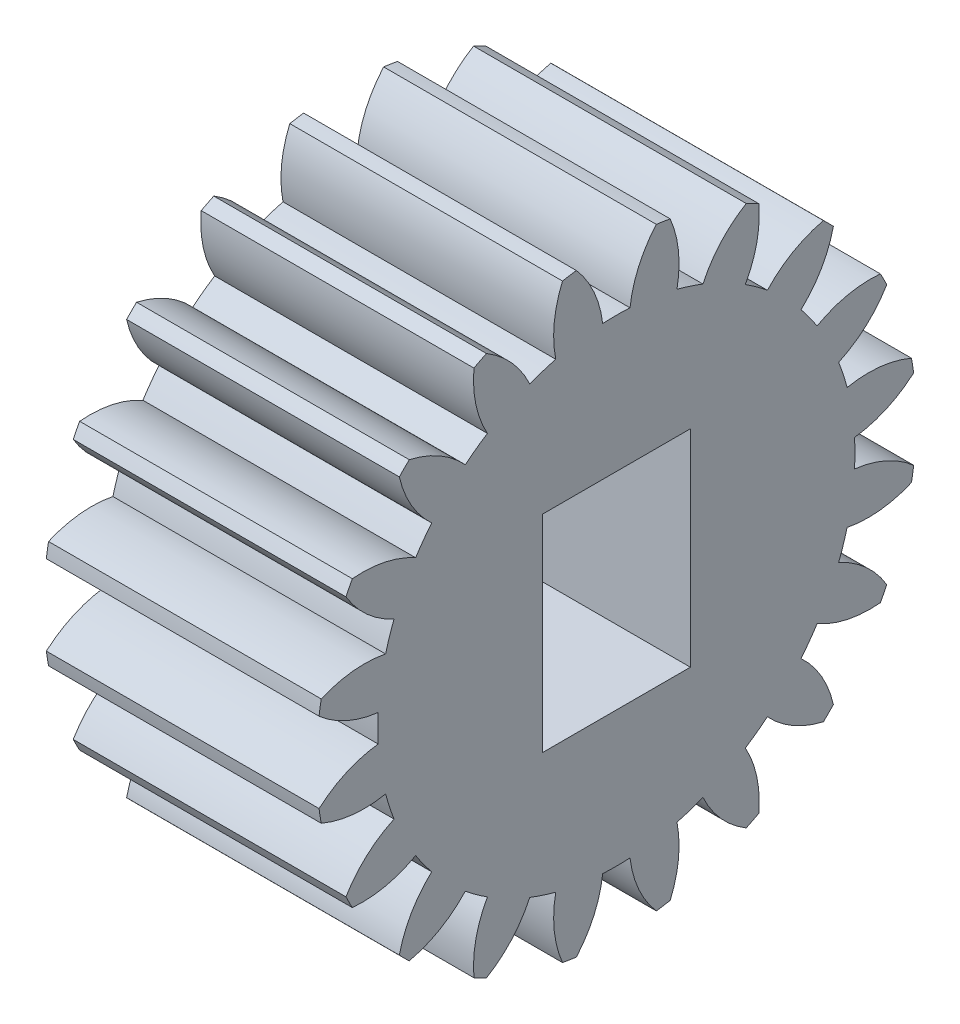
SolidWorks part; units mm, degrees
ref_plane "Plane1" through (0, 0, 0) normal (0, 0, 1) x (1, 0, 0)
ref_plane "Plane2" through (0, 0, 0) normal (0, 1, 0) x (1, 0, 0)
ref_plane "Plane3" through (0, 0, 0) normal (1, 0, 0) x (0, 0, -1)
other "Configuration Table"
sketch "HoldingSke" plane through (0, 0, 0) normal (0, 1, 0) x (1, 0, 0)
  line L0 (0, 0) -> (1.3424, -0.4886)
  line L1 (-15, 0) -> (100, 0) construction
  line L2 (0, 0) -> (-2.1039, 2.3779)
  line L3 (0, 0) -> (-11.863, 4.5341)
  line L4 (0, 0) -> (8.1152, 2.9537)
  line L5 (0, 0) -> (-46.8476, -17.4728)
  line L6 (0, 0) -> (-5.8027, -3.9151)
  line L7 (-2.1039, 2.3779) -> (8.6586, 51.2059)
  line L8 (-76.2, 54.61) -> (-76.1, 54.61)
  line L9 (-71.009, 38.7566) -> (-53.1078, 45.2721)
  line L10 (-76.2, 71.12) -> (104.1128, 71.12)
  line L11 (0, 0) -> (-7, 0)
  line L12 (-76.2, 101.6) -> (-76.173, 101.6)
  line L13 (24.9733, 27.94) -> (52.9518, 28.4284)
  line L14 (24.9733, 27.94) -> (24.9743, 27.94)
  line L15 (24.9733, 27.94) -> (100.4006, 29.5858)
  line L16 (-63.627, -0.7) -> (-12.827, -0.7)
  circle A0 centre (0, 0) radius 0.5
  circle A1 centre (0, 0) radius 6.124
  circle A2 centre (0, 0) radius 37.5
  circle A3 centre (0, 0) radius 0.5
  dimension "MHD" = 12.248
  dimension "Hub_dia" = 75
  dimension "Bore" = 1
  dimension "MBD" = 1
  dimension "Num_teeth" = 20
  dimension "Pitch" = 1.4286
  dimension "Overall_len" = 50
  dimension "Show_teeth" = 20
  dimension "Thickness" = 7
  dimension "OAL" = 50.0001
  dimension "T_dim" = 0.1
  dimension "Ap" = 20
  dimension "H" = 19.05
  dimension "Pitch_radius" = 180.3128
  dimension "Width" = 7
  dimension "Backlash" = 0.027
  dimension "Addendum_fac" = 1
  dimension "Dedendum_fac" = 1.25
  dimension "Clearance_fac" = 0.25
  dimension "Dedendum_add" = 0.001
  dimension "Module" = 0.7
sketch "BasProSke" plane through (0, 0, 0) normal (0, 1, 0) x (1, 0, 0)
  line L0 (-10, 0) -> (60, 0) construction
  line L1 (0, 0) -> (0, 7.7)
  line L2 (0, 0) -> (7, 0)
  line L3 (7, 0) -> (7, 7.7)
  line L4 (7, 7.7) -> (0, 7.7)
  dimension "Thickness" = 7
  dimension "Diameter" = 15.4
revolve "Base-Revolve" add sketch "BasProSke" angle 360 about L0
sketch "TooCutSke" plane through (0, 0, 0) normal (1, 0, 0) x (0, 0, -1)
  line L1 (0, 0) -> (0, 107) construction
  line L2 (0, 0) -> (-0.5964, 6.9745) construction
  line L3 (0, 0) -> (-2.1844, 13.792) construction
  line L4 (-0.5964, 6.9745) -> (-1.0922, 6.896) construction
  arc A0 (0.3505, 6.114) -> (-0.3505, 6.114) centre (0, 0) ccw
  arc A1 (1.0465, 7.6542) -> (-1.0465, 7.6542) centre (0, 0) ccw
  circle A2 centre (0, 0) radius 7 construction
  circle A3 centre (0, 0) radius 6.5778 construction
  arc A4 (-0.3505, 6.114) -> (-1.0465, 7.6542) centre (-3.1311, 5.7848) ccw
  arc A5 (1.0465, 7.6542) -> (0.3505, 6.114) centre (3.1311, 5.7848) ccw
  dimension "Root_dia" = 12.248
  dimension "Overcut_dia" = 15.4508
  dimension "Pitch_dia" = 14
  dimension "Base_dia" = 13.1557
  dimension "Flank_rad" = 2.8
  dimension "Half_ang" = 9
  dimension "Half_CT" = 0.502
extrude "ToothCut" cut sketch "TooCutSke" along normal through all
fillet "Breaks" [suppressed] radius 0.014
fillet "RootFillets" [suppressed] radius 0.176
pattern_circular "TeethCuts" count 20 every 18 about axis through (-10, 0, 0) along (1, 0, 0) of "ToothCut", "RootFillets", "Breaks"
sketch "HubNeaOneSke" plane through (0, 0, 0) normal (-1, 0, 0) x (0, 0, 1)
  circle A0 centre (0, 0) radius 6.124
  dimension "Diameter" = 12.248
extrude "HubNearOne" [suppressed] add sketch "HubNeaOneSke" along normal blind 43.0001
sketch "HubNeaBotSke" plane through (0, 0, 0) normal (-1, 0, 0) x (0, 0, 1)
  circle A0 centre (0, 0) radius 6.124
  dimension "Diameter" = 12.248
extrude "HubNearBoth" [suppressed] add sketch "HubNeaBotSke" along normal blind 21.5
ref_plane "FarPln" through (7, 0, 0) normal (1, 0, 0) x (0, 0, -1)
sketch "HubFarSke" plane through (7, 0, 0) normal (1, 0, 0) x (0, 0, -1)
  circle A0 centre (0, 0) radius 6.124
  dimension "Diameter" = 12.248
extrude "HubFar" [suppressed] add sketch "HubFarSke" along normal blind 21.5
sketch "BorSke" plane through (0, 0, 0) normal (1, 0, 0) x (0, 0, -1)
  circle A0 centre (0, 0) radius 0.5
  dimension "Diameter" = 1
extrude "Bore" cut sketch "BorSke" along normal mid plane 100.0001
sketch "KeySke" plane through (0, 0, 0) normal (1, 0, 0) x (0, 0, -1)
  line L0 (-0.05, 0) -> (-0.05, 0.6)
  line L1 (-0.05, 0.6) -> (0.05, 0.6)
  line L2 (0.05, 0.6) -> (0.05, 0)
  line L3 (0, 0) -> (0, 34) construction
  line L4 (-0.05, 0) -> (0.05, 0)
  dimension "Offset" = 0.6
  dimension "Width" = 0.1
extrude "Keyway" [suppressed] cut sketch "KeySke" along normal mid plane 100.0001
pattern_circular "Keyway2" [suppressed] count 2 every 90 about axis through (-10, 0, 0) along (1, 0, 0)
sketch "Sketch1" plane through (7, 0, 0) normal (1, 0, 0) x (0, 0, -1)
  line L1 (1.9, -2.65) -> (-1.9, -2.65)
  line L2 (1.9, -2.65) -> (1.9, 2.65)
  line L3 (1.9, 2.65) -> (-1.9, 2.65)
  line L4 (-1.9, -2.65) -> (-1.9, 2.65)
  line L5 (1.9, -2.65) -> (-1.9, 2.65) construction
  line L6 (1.9, 2.65) -> (-1.9, -2.65) construction
  point P0 (0, 0)
  dimension "D1" = 3.8
  dimension "D2" = 5.3
extrude "Cut-Extrude1" cut sketch "Sketch1" against normal through all both and the other way through all
equation "' \"Module@HoldingSke\" = 6.35"
equation "' \"Num_teeth@HoldingSke\" = 12"
equation "' \"Ap@HoldingSke\" =  20"
equation "' \"Ap@HoldingSke\" = 20"
equation "' \"Width@HoldingSke\" = 0.5 * 25.4"
equation "' \"Hub_dia@HoldingSke\"= 1 * 25.4"
equation "' \"Hub_dia@HoldingSke\" = 1 * 25.4"
equation "' \"Overall_len@HoldingSke\" = 1.0 * 25.4"
equation "' \"Bore@HoldingSke\" = 0.75 * 25.4"
equation "' \"T_dim@HoldingSke\" = 0.1 * 25.4"
equation "' \"Width@KeySke\" = 0.25 * 25.4"
equation "' \"Show_teeth@HoldingSke\" = 13"
equation "' \"Backlash@HoldingSke\" = 0.009 * 25.4"
equation "' \"Addendum_fac@HoldingSke\" = 1.0"
equation "' \"Dedendum_fac@HoldingSke\" = 1.25"
equation "' \"Dedendum_add@HoldingSke\" = 0.00005 * 25.4"
equation "' \"Clearance_fac@HoldingSke\" = 0.25"
equation "\"Pitch@HoldingSke\" = 1 / \"Module@HoldingSke\""
equation "\"Overcut_dia@TooCutSke\" = (\"Num_teeth@HoldingSke\" + 2 * \"Addendum_fac@HoldingSke\") / \"Pitch@HoldingSke\" + 0.002 * 25.4"
equation "\"Pitch_dia@TooCutSke\" = \"Num_teeth@HoldingSke\" / \"Pitch@HoldingSke\""
equation "\"Base_dia@TooCutSke\" = \"Num_teeth@HoldingSke\" / \"Pitch@HoldingSke\" * cos((\"Ap@HoldingSke\"  * 3.14159265 / 180))"
equation "\"Root_dia@TooCutSke\" = (\"Num_teeth@HoldingSke\" + 2) / \"Pitch@HoldingSke\" - 2 * (\"Addendum_fac@HoldingSke\" + \"Dedendum_fac@HoldingSke\") / \"Pitch@HoldingSke\" - \"Dedendum_add@HoldingSke\" * 2"
equation "\"Half_ang@TooCutSke\" = 180 / \"Num_teeth@HoldingSke\""
equation "\"Half_CT@TooCutSke\" = \"Num_teeth@HoldingSke\" / \"Pitch@HoldingSke\" * sin((3.14159265 / 2 / \"Num_teeth@HoldingSke\")) / 2 - 7 * \"Backlash@HoldingSke\" / 4"
equation "\"Flank_rad@TooCutSke\" = \"Num_teeth@HoldingSke\" / \"Pitch@HoldingSke\" / 5"
equation "\"Radius@RootFillets\" = \"Clearance_fac@HoldingSke\" / \"Pitch@HoldingSke\" + \"Dedendum_add@HoldingSke\""
equation "\"Break_rad@Breaks\" = 0.02 / \"Pitch@HoldingSke\""
equation "\"Thickness@HoldingSke\" = \"Width@HoldingSke\""
equation "\"OAL@HoldingSke\" = \"Thickness@HoldingSke\""
equation "\"MHD@HoldingSke\" = (\"Num_teeth@HoldingSke\" + 2) / \"Pitch@HoldingSke\" - 2 * (\"Addendum_fac@HoldingSke\" + \"Dedendum_fac@HoldingSke\")  / \"Pitch@HoldingSke\" - \"Dedendum_add@HoldingSke\" * 2"
equation "\"MBD@HoldingSke\" = (\"Num_teeth@HoldingSke\" + 2) / \"Pitch@HoldingSke\" - 2 * (\"Addendum_fac@HoldingSke\" + \"Dedendum_fac@HoldingSke\")  / \"Pitch@HoldingSke\" - \"Dedendum_add@HoldingSke\" * 2 - 0.002 * 25.4"
equation "\"MHD@HoldingSke\" = ((sgn( \"MHD@HoldingSke\" - \"Hub_dia@HoldingSke\" )-1)*( \"MHD@HoldingSke\" - \"Hub_dia@HoldingSke\" ))/-2+ \"Hub_dia@HoldingSke\""
equation "\"MBD@HoldingSke\" = ((sgn( \"MBD@HoldingSke\" - \"Bore@HoldingSke\" )-1)*( \"MBD@HoldingSke\" - \"Bore@HoldingSke\" ))/-2+ \"Bore@HoldingSke\""
equation "\"OAL@HoldingSke\" = ((sgn( \"OAL@HoldingSke\" - \"Overall_len@HoldingSke\" )+1)*( \"OAL@HoldingSke\" - \"Overall_len@HoldingSke\" ))/2 + \"Overall_len@HoldingSke\" + 0.000002 * 25.4"
equation "\"Num_teeth@TeethCuts\" = int( \"Show_teeth@HoldingSke\" ) + 1"
equation "\"Num_teeth@TeethCuts\" = ((sgn( \"Num_teeth@TeethCuts\" - \"Num_teeth@HoldingSke\" )-1)*( \"Num_teeth@TeethCuts\" - \"Num_teeth@HoldingSke\" ))/-2+ \"Num_teeth@HoldingSke\""
equation "\"Num_teeth@TeethCuts\" = ((sgn( \"Num_teeth@TeethCuts\" - 2.0)+1)*( \"Num_teeth@TeethCuts\" - 2.0))/2 +2.0"
equation "\"Angle@TeethCuts\" = 360.0 / \"Num_teeth@HoldingSke\""
equation "\"Diameter@BasProSke\" = (\"Num_teeth@HoldingSke\" + 2 * \"Addendum_fac@HoldingSke\") / \"Pitch@HoldingSke\""
equation "\"Thickness@BasProSke\"  = \"Thickness@HoldingSke\""
equation "' \"Fillet_rad@BasProSke\" =  \"Thickness@HoldingSke\" * 0.05"
equation "' \"Fillet_rad@BasProSke\" = \"Thickness@HoldingSke\" * 0.05"
equation "\"MHD@HoldingSke\" = ((sgn( \"MHD@HoldingSke\" - \"Root_dia@TooCutSke\" )-1)*( \"MHD@HoldingSke\" - \"Root_dia@TooCutSke\" ))/-2+ \"Root_dia@TooCutSke\""
equation "\"Diameter@HubNeaOneSke\" = \"MHD@HoldingSke\""
equation "\"Length@HubNearOne\" = \"OAL@HoldingSke\" - \"Thickness@BasProSke\""
equation "\"Diameter@HubNeaBotSke\" = \"MHD@HoldingSke\""
equation "\"Length@HubNearBoth\" = ( \"OAL@HoldingSke\" - \"Thickness@BasProSke\" ) / 2.0"
equation "\"Thickness@FarPln\" = \"Thickness@BasProSke\""
equation "\"Diameter@HubFarSke\" = \"MHD@HoldingSke\""
equation "\"Length@HubFar\" = ( \"OAL@HoldingSke\" - \"Thickness@BasProSke\" ) / 2.0"
equation "\"Diameter@BorSke\" = \"MBD@HoldingSke\""
equation "\"D1@Bore\" = \"OAL@HoldingSke\" * 2.0"
equation "\"D1@Keyway\" = \"OAL@HoldingSke\" * 2.0"
equation "\"Offset@KeySke\" = \"T_dim@HoldingSke\" + \"MBD@HoldingSke\" / 2.0"
